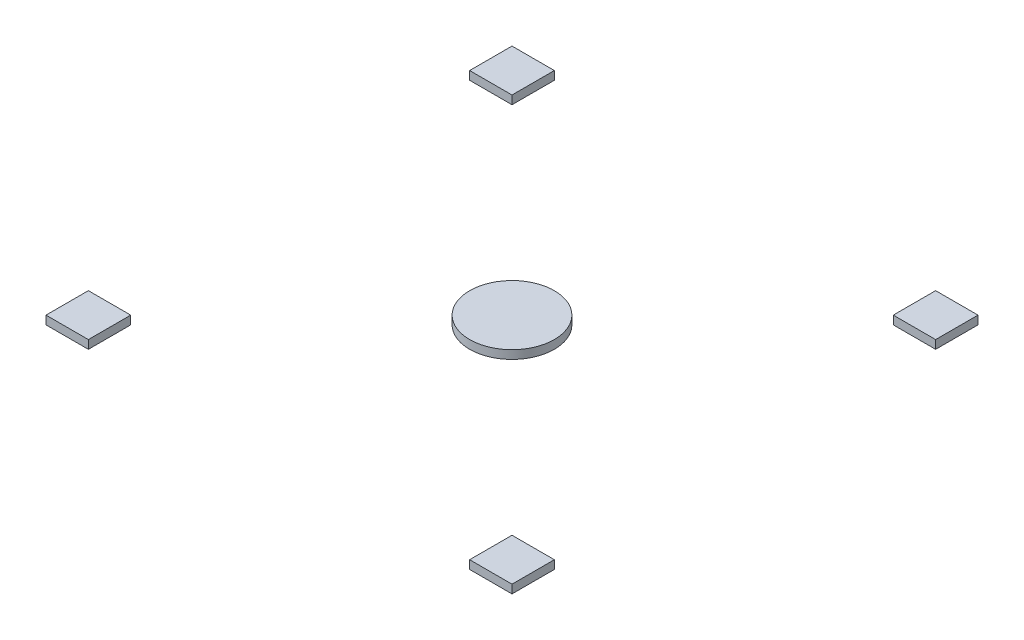
SolidWorks part; units mm, degrees
ref_plane "Ebene vorne" through (0, 0, 0) normal (0, 0, 1) x (1, 0, 0)
ref_plane "Ebene oben" through (0, 0, 0) normal (0, 1, 0) x (1, 0, 0)
ref_plane "Ebene rechts" through (0, 0, 0) normal (1, 0, 0) x (0, 0, -1)
sketch "Skizze1" plane through (0, 0, 0) normal (0, 1, 0) x (1, 0, 0)
  line L0 (0, 0) -> (0, 50) construction
  line L1 (0, 50) -> (-50, 50) construction
  line L2 (-50, 50) -> (0, 0) construction
  line L3 (55, 45) -> (55, 55)
  line L4 (-45, 55) -> (-55, 55)
  line L5 (-45, 55) -> (-45, 45)
  line L6 (-45, 45) -> (-55, 45)
  line L7 (-55, 55) -> (-55, 45)
  line L8 (-45, 55) -> (-55, 45) construction
  line L9 (-45, 45) -> (-55, 55) construction
  line L10 (55, 45) -> (45, 45)
  line L11 (45, 45) -> (45, 55)
  line L12 (55, 55) -> (45, 55)
  line L13 (50, 0) -> (50, 50) construction
  line L14 (0, 0) -> (50, 0) construction
  line L15 (55, 45) -> (45, 55) construction
  line L16 (50, 50) -> (0, 0) construction
  line L17 (45, 45) -> (55, 55) construction
  line L18 (45, -55) -> (55, -55)
  line L19 (45, -55) -> (45, -45)
  line L20 (45, -45) -> (55, -45)
  line L21 (55, -55) -> (55, -45)
  line L22 (0, -50) -> (50, -50) construction
  line L23 (0, 0) -> (0, -50) construction
  line L24 (45, -55) -> (55, -45) construction
  line L25 (50, -50) -> (0, 0) construction
  line L26 (45, -45) -> (55, -55) construction
  line L27 (-55, -45) -> (-55, -55)
  line L28 (-55, -45) -> (-45, -45)
  line L29 (-45, -45) -> (-45, -55)
  line L30 (-55, -55) -> (-45, -55)
  line L31 (-50, 0) -> (-50, -50) construction
  line L32 (0, 0) -> (-50, 0) construction
  line L33 (-55, -45) -> (-45, -55) construction
  line L34 (-50, -50) -> (0, 0) construction
  line L35 (-45, -45) -> (-55, -55) construction
  circle A0 centre (0, 0) radius 10
  point P29 (0, 0)
  dimension "D4" = 20
  dimension "D1" = 10
  dimension "D3" = 100
  dimension "D2" = 4
extrude "Aufsatz-Linear austragen1" add sketch "Skizze1" along normal blind 2
